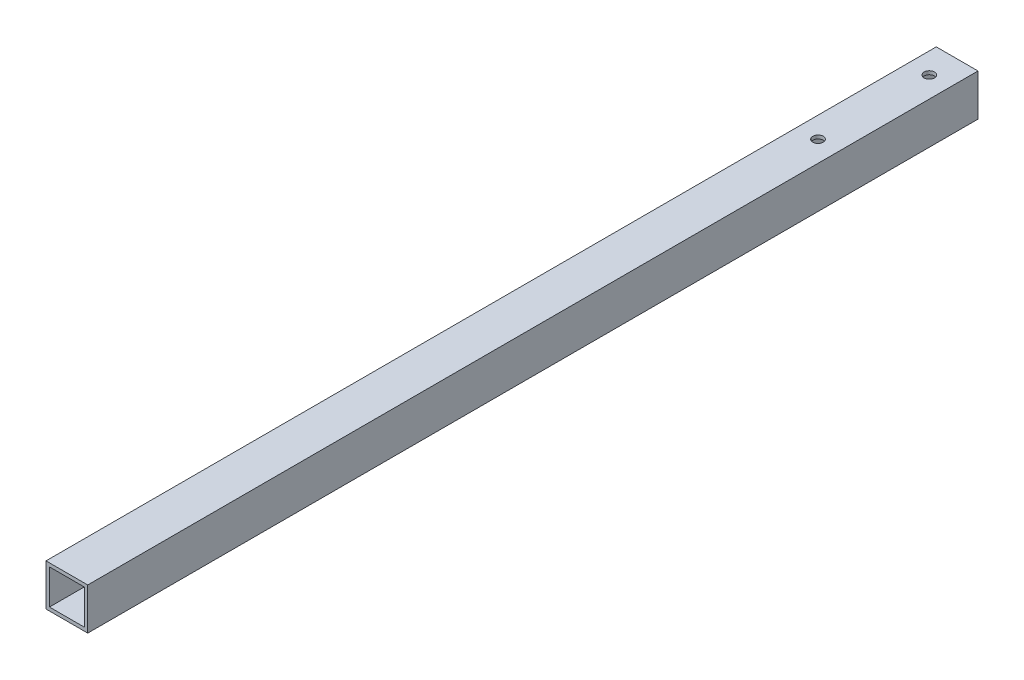
SolidWorks part; units mm, degrees
material "6061 Alloy"
ref_plane "Front Plane" through (0, 0, 0) normal (0, 0, 1) x (1, 0, 0)
ref_plane "Top Plane" through (0, 0, 0) normal (0, 1, 0) x (1, 0, 0)
ref_plane "Right Plane" through (0, 0, 0) normal (1, 0, 0) x (0, 0, -1)
sketch "Sketch1" plane through (0, 0, 0) normal (0, 0, 1) x (1, 0, 0)
  line L1 (-7.9375, -7.9375) -> (7.9375, -7.9375)
  line L2 (-7.9375, -7.9375) -> (-7.9375, 7.9375)
  line L3 (-7.9375, 7.9375) -> (7.9375, 7.9375)
  line L4 (7.9375, -7.9375) -> (7.9375, 7.9375)
  line L5 (-7.9375, -7.9375) -> (7.9375, 7.9375) construction
  line L6 (-7.9375, 7.9375) -> (7.9375, -7.9375) construction
  line L7 (-9.525, -9.525) -> (9.525, -9.525)
  line L8 (-9.525, -9.525) -> (-9.525, 9.525)
  line L9 (-9.525, 9.525) -> (9.525, 9.525)
  line L10 (9.525, -9.525) -> (9.525, 9.525)
  line L11 (-9.525, -9.525) -> (9.525, 9.525) construction
  line L12 (-9.525, 9.525) -> (9.525, -9.525) construction
  point P0 (0, 0)
  point P6 (0, 0)
  dimension "D1" = 19.05
  dimension "D2" = 19.05
  dimension "D3" = 1.5875
  dimension "D4" = 1.5875
extrude "Boss-Extrude1" add sketch "Sketch1" along normal blind 406.4
sketch "Sketch2" plane through (0, 0, 0) normal (0, 1, 0) x (1, 0, 0)
  line L0 (0, 0) -> (0, -12.7) construction
  line L1 (0, 0) -> (0, -63.5) construction
  circle A1 centre (0, -12.7) radius 2.3813
  circle A2 centre (0, -63.5) radius 2.3812
extrude "Cut-Extrude1" cut sketch "Sketch2" against normal through all both and the other way through all
